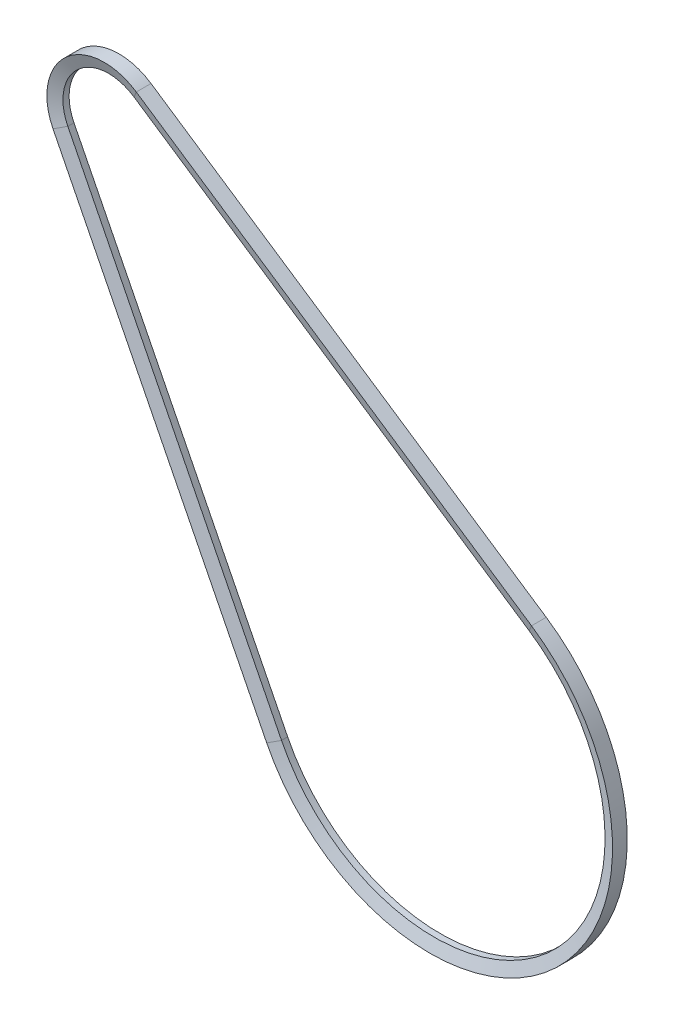
SolidWorks part; units mm, degrees
ref_plane "Front Plane" through (0, 0, 0) normal (0, 0, 1) x (1, 0, 0)
ref_plane "Top Plane" through (0, 0, 0) normal (0, 1, 0) x (1, 0, 0)
ref_plane "Right Plane" through (0, 0, 0) normal (1, 0, 0) x (0, 0, -1)
sketch "Sketch2" plane through (0, 0, 0) normal (0, 0, 1) x (1, 0, 0)
  line L0 (0, 0) -> (1, 0) construction
  line L1 (0, 0) -> (0, 1) construction
  line L2 (16.693, 24.9267) -> (284.99, -154.7475)
  line L3 (118.2576, -301.9623) -> (-26.8024, -13.4771)
  arc A0 (-26.8024, -13.4771) -> (16.693, 24.9267) centre (0, 0) cw
  arc A1 (284.99, -154.7475) -> (118.2576, -301.9623) centre (221, -250.3) cw
ref_plane "Plane1" through (16.693, 24.9267, 0) normal (0.8309, -0.5564, 0) x (0, 0, -1)
sketch "Sketch3" plane through (16.693, 24.9267, 0) normal (0.8309, -0.5564, 0) x (0, 0, -1)
  line L0 (2.0882, 1) -> (-2.0882, 1)
  line L1 (-2.0882, 1) -> (-5, 9)
  line L2 (-5, 9) -> (5, 9)
  line L3 (5, 9) -> (2.0882, 1)
  line L4 (0, 1) -> (0, 12.8267) construction
  line L5 (0, 0) -> (0, 1.2335) construction
  dimension "D1" = 8
  dimension "D2" = 1
  dimension "D3" = 40
  dimension "D4" = 10
sweep "Sweep1" add profiles "Sketch3" path "Sketch2"
